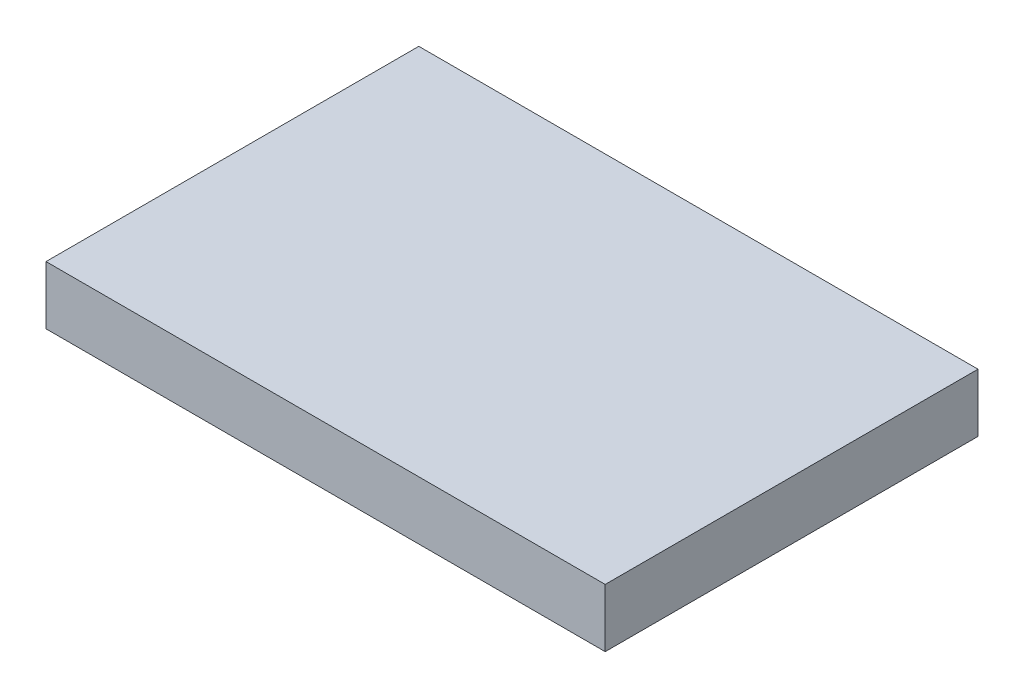
SolidWorks part; units mm, degrees
ref_plane "Front Plane" through (0, 0, 0) normal (0, 0, 1) x (1, 0, 0)
ref_plane "Top Plane" through (0, 0, 0) normal (0, 1, 0) x (1, 0, 0)
ref_plane "Right Plane" through (0, 0, 0) normal (1, 0, 0) x (0, 0, -1)
sketch "Sketch1" plane through (0, 0, 0) normal (0, 1, 0) x (1, 0, 0)
  line L1 (0, 0) -> (12, 0)
  line L2 (0, 0) -> (0, 8)
  line L3 (0, 8) -> (12, 8)
  line L4 (12, 0) -> (12, 8)
  dimension "D1" = 8
  dimension "D2" = 12
extrude "Boss-Extrude1" add sketch "Sketch1" along normal blind 1.25
